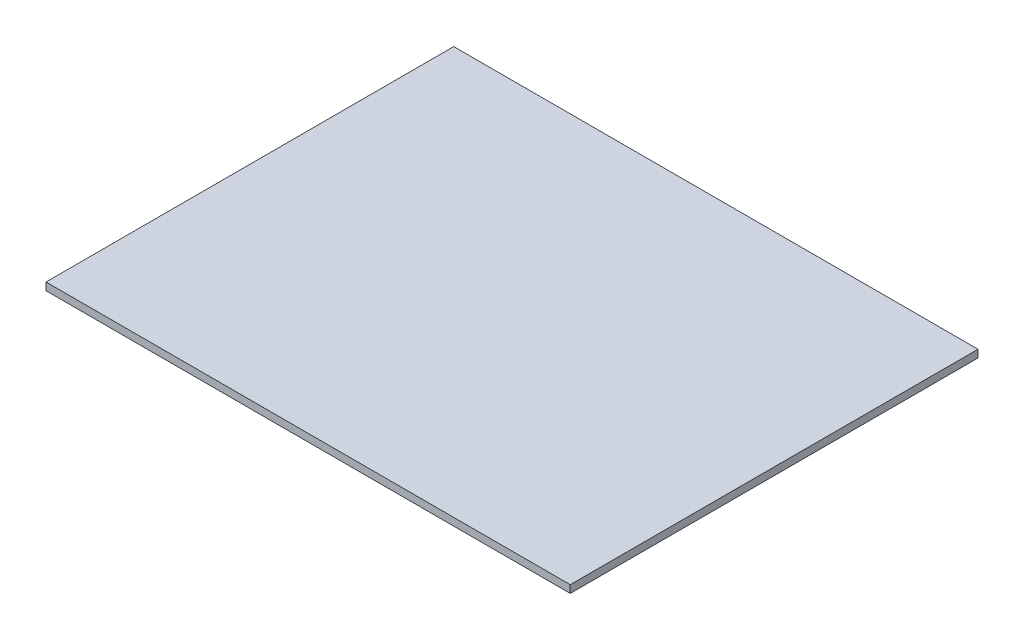
SolidWorks part; units mm, degrees
ref_plane "Front Plane" through (0, 0, 0) normal (0, 0, 1) x (1, 0, 0)
ref_plane "Top Plane" through (0, 0, 0) normal (0, 1, 0) x (1, 0, 0)
ref_plane "Right Plane" through (0, 0, 0) normal (1, 0, 0) x (0, 0, -1)
sketch "Sketch1" plane through (0, 0, 0) normal (0, 1, 0) x (1, 0, 0)
  line L1 (0, 0) -> (45, 0)
  line L2 (0, 0) -> (0, 35)
  line L3 (0, 35) -> (45, 35)
  line L4 (45, 0) -> (45, 35)
  dimension "D1" = 45
  dimension "D2" = 35
extrude "Boss-Extrude1" add sketch "Sketch1" along normal blind 0.65
